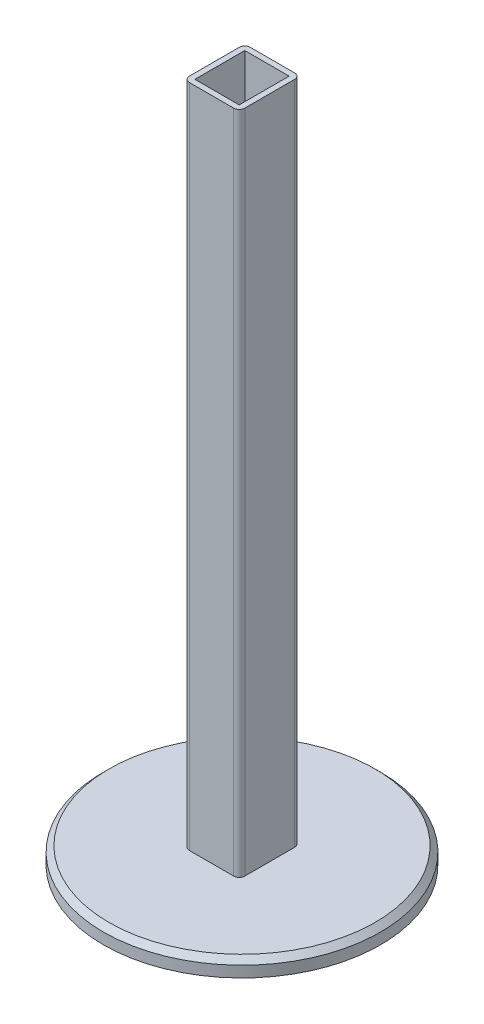
SolidWorks part; units mm, degrees
ref_plane "Front Plane" through (0, 0, 0) normal (0, 0, 1) x (1, 0, 0)
ref_plane "Top Plane" through (0, 0, 0) normal (0, 1, 0) x (1, 0, 0)
ref_plane "Right Plane" through (0, 0, 0) normal (1, 0, 0) x (0, 0, -1)
sketch "Sketch1" plane through (0, 0, 0) normal (0, 1, 0) x (1, 0, 0)
  circle A0 centre (0, 0) radius 250
extrude "Boss-Extrude1" add sketch "Sketch1" along normal blind 30
sketch "Sketch2" plane through (0, 30, 0) normal (0, 1, 0) x (1, 0, 0)
  line L1 (50, 55) -> (-50, 55)
  line L2 (50, 55) -> (50, -55)
  line L3 (50, -55) -> (-50, -55)
  line L4 (-50, 55) -> (-50, -55)
  line L5 (50, 55) -> (-50, -55) construction
  line L6 (50, -55) -> (-50, 55) construction
  point P0 (0, 0)
extrude "Boss-Extrude2" add sketch "Sketch2" along normal blind 1200
chamfer "Chamfer1" distance 10 angle 45 1 edges at (0, 30, 250)
fillet "Fillet1" radius 10 4 edges at (-50, 630, -55) (-50, 630, 55) (50, 630, -55) (50, 630, 55)
sketch "Sketch3" plane through (0, 1230, 0) normal (0, 1, 0) x (1, 0, 0)
  line L1 (40, 45) -> (-40, 45)
  line L2 (40, 45) -> (40, -45)
  line L3 (40, -45) -> (-40, -45)
  line L4 (-40, 45) -> (-40, -45)
  line L5 (40, 45) -> (-40, -45) construction
  line L6 (40, -45) -> (-40, 45) construction
  line L7 (-50, 45) -> (-50, -45) construction
  line L8 (-40, -55) -> (40, -55) construction
  point P0 (0, 0)
  dimension "D1" = 10
  dimension "D2" = 10
extrude "Cut-Extrude1" cut sketch "Sketch3" against normal blind 1170
